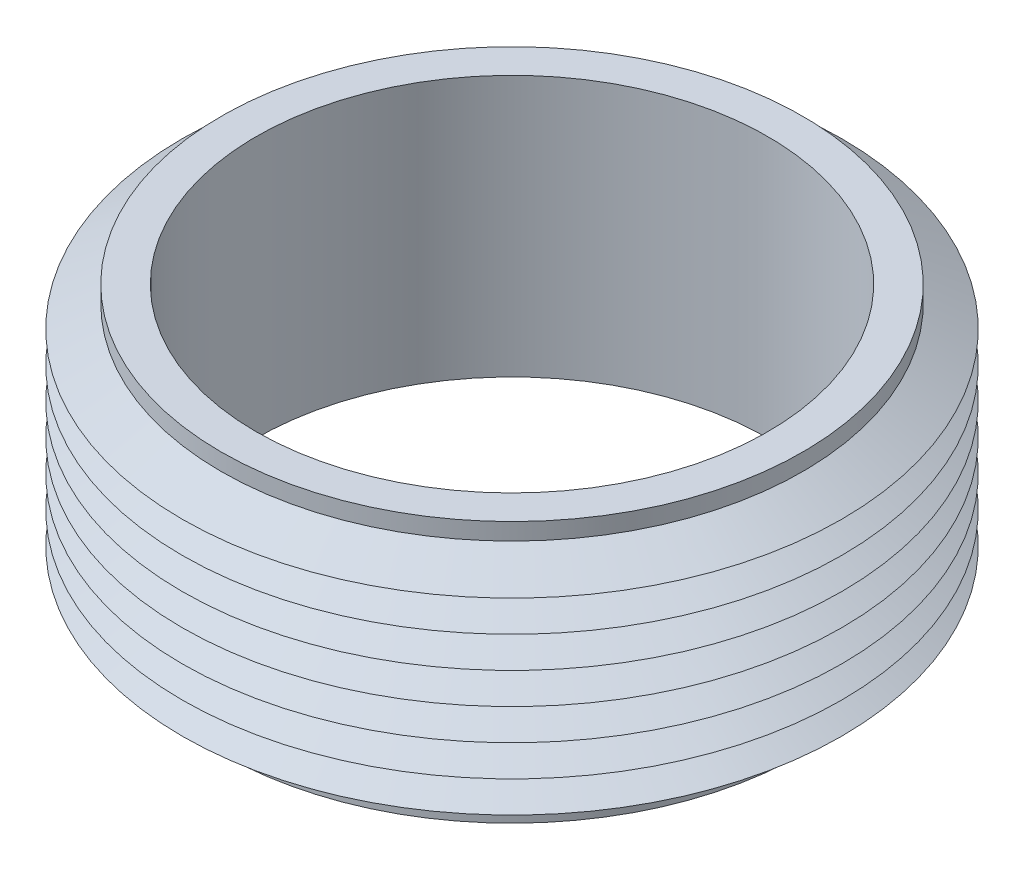
SolidWorks part; units mm, degrees
ref_plane "Front Plane" through (0, 0, 0) normal (0, 0, 1) x (1, 0, 0)
ref_plane "Top Plane" through (0, 0, 0) normal (0, 1, 0) x (1, 0, 0)
ref_plane "Right Plane" through (0, 0, 0) normal (1, 0, 0) x (0, 0, -1)
ref_axis "Axis1" through (0, 76.3195, 0) along (0, -1, 0)
sketch "Sketch1" plane through (0, 0, 0) normal (0, 0, 1) x (1, 0, 0)
  line L0 (40.5, 0) -> (40.5, 2)
  line L1 (55, 0) -> (-55, 0) construction
  line L2 (40.5, 2) -> (44.8581, 4.0177)
  line L3 (44.8581, 4.0177) -> (40.5, 6.4687)
  line L4 (40.5, 6.4687) -> (44.8581, 8.4864)
  line L5 (44.8581, 8.4864) -> (40.5, 10.9374)
  line L6 (40.5, 10.9374) -> (44.8581, 12.9551)
  line L7 (44.8581, 12.9551) -> (40.5, 15.4061)
  line L8 (40.5, 15.4061) -> (44.8581, 17.4238)
  line L9 (44.8581, 17.4238) -> (40.5, 19.8748)
  line L10 (40.5, 19.8748) -> (44.8581, 21.8925)
  line L11 (44.8581, 21.8925) -> (40.5, 24.3435)
  line L12 (40.5, 24.3435) -> (44.8581, 26.3612)
  line L13 (44.8581, 26.3612) -> (40.5, 28.8122)
  line L14 (40.5, 28.8122) -> (44.8581, 30.8299)
  line L15 (44.8581, 30.8299) -> (40.5, 33.2809)
  line L16 (40.5, 33.2809) -> (40.5, 35.2809)
  line L17 (0, -55) -> (0, 55) construction
  line L18 (40.5, 35.2809) -> (37.5, 35.2809)
  line L19 (40.5, 0) -> (37.5, 0)
  line L20 (37.5, 35.2809) -> (37.5, 0)
  line L21 (44.8581, 30.8299) -> (40.5, 30.8299) construction
  line L22 (40.5, 0) -> (40.5, 35.2809) construction
  line L23 (44.8581, 26.3612) -> (40.5, 26.3612) construction
  line L24 (44.8581, 21.8925) -> (40.5, 21.8925) construction
  line L25 (44.8581, 17.4238) -> (40.5, 17.4238) construction
  line L26 (44.8581, 12.9551) -> (40.5, 12.9551) construction
  line L27 (44.8581, 4.0177) -> (40.5, 4.0177) construction
  point P21 (44.8581, 30.8299)
  dimension "D1" = 2
  dimension "D2" = 2
  dimension "D3" = 40.5
  dimension "D4" = 3
  dimension "D5" = 3
  dimension "D6" = 5
revolve "Revolve-Thin1" add sketch "Sketch1" angle 360 about axis through (0, 76.3195, 0) along (0, -1, 0)
ref_plane "Plane1" through (0, 36.2809, 0) normal (0, 1, 0) x (1, 0, 0)
